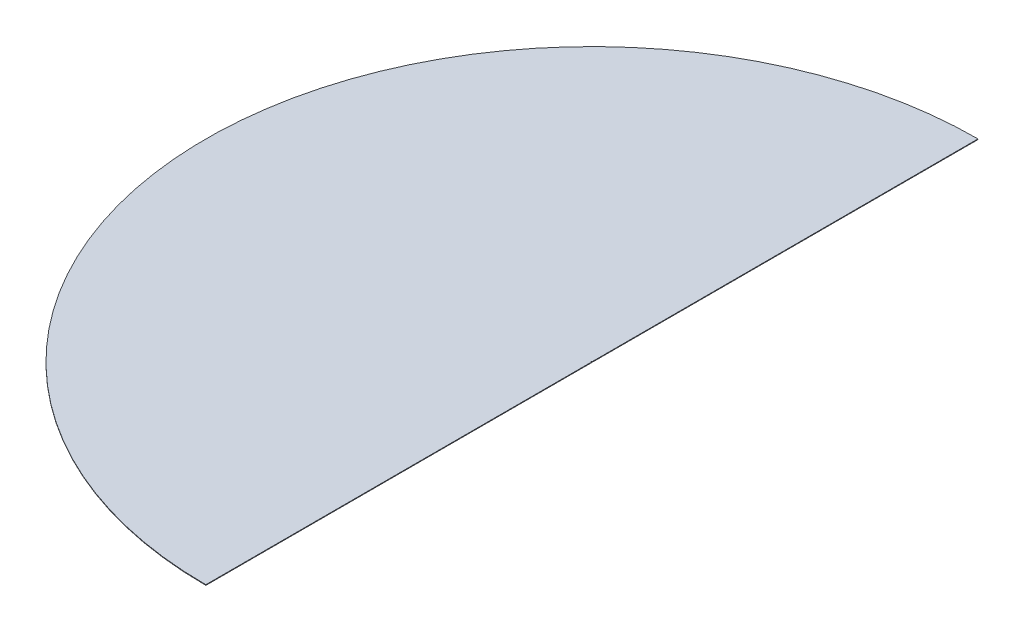
SolidWorks part; units mm, degrees
ref_plane "Front Plane" through (0, 0, 0) normal (0, 0, 1) x (1, 0, 0)
ref_plane "Top Plane" through (0, 0, 0) normal (0, 1, 0) x (1, 0, 0)
ref_plane "Right Plane" through (0, 0, 0) normal (1, 0, 0) x (0, 0, -1)
sketch "Sketch1" plane through (0, 0, 0) normal (0, 1, 0) x (1, 0, 0)
  line L0 (0, 20000) -> (0, 28.5)
  line L1 (0, -28.5) -> (0, -20000)
  arc A0 (0, 20000) -> (0, -20000) centre (0, 0) ccw
  arc A1 (0, 28.5) -> (0, -28.5) centre (0, 0) ccw
  dimension "D1" = 57
  dimension "D2" = 40000
extrude "Boss-Extrude1" add sketch "Sketch1" along normal blind 31.5
